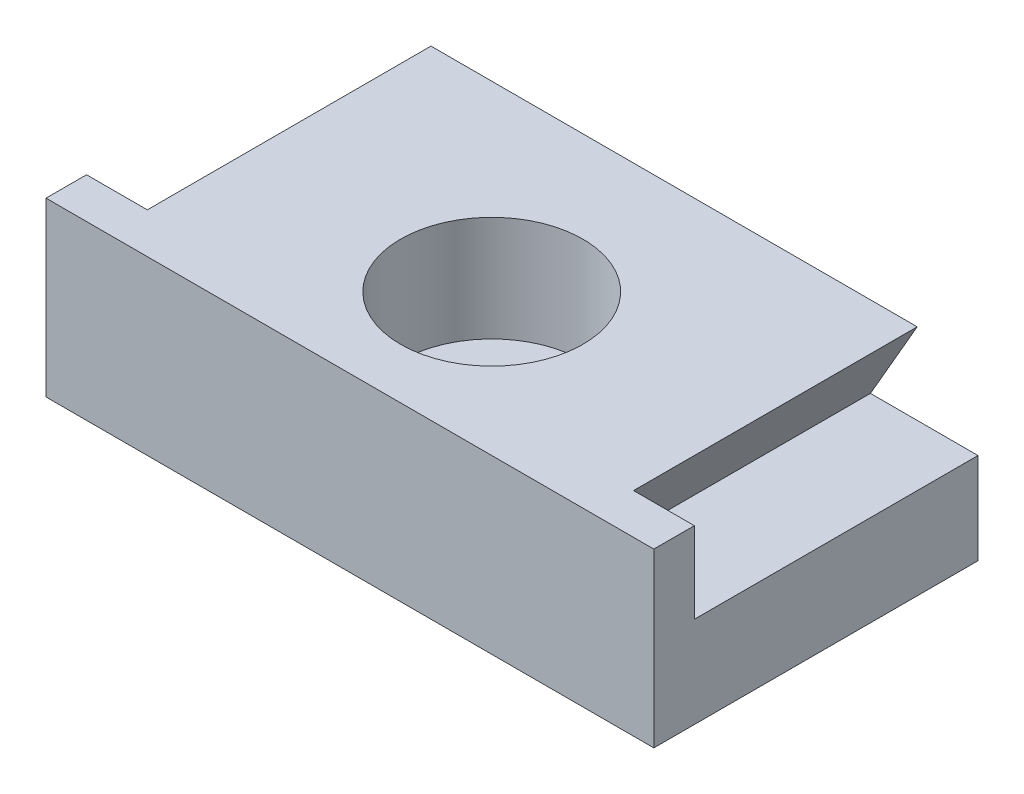
SolidWorks part; units mm, degrees
ref_plane "Front Plane" through (0, 0, 0) normal (0, 0, 1) x (1, 0, 0)
ref_plane "Top Plane" through (0, 0, 0) normal (0, 1, 0) x (1, 0, 0)
ref_plane "Right Plane" through (0, 0, 0) normal (1, 0, 0) x (0, 0, -1)
sketch "Sketch1" plane through (0, 0, 0) normal (0, 1, 0) x (1, 0, 0)
  line L1 (0, 0) -> (30, 0)
  line L2 (0, 0) -> (0, 16)
  line L3 (0, 16) -> (30, 16)
  line L4 (30, 0) -> (30, 16)
  dimension "D1" = 30
  dimension "D2" = 16
extrude "Boss-Extrude1" add sketch "Sketch1" along normal blind 8.5
sketch "Sketch2" plane through (0, 8.5, 0) normal (0, 1, 0) x (1, 0, 0)
  line L0 (0, 0) -> (30, 0) construction
  circle A0 centre (15, 7) radius 4.5
  point P5 (15, 0)
  dimension "D1" = 9
  dimension "D2" = 7
extrude "Cut-Extrude1" cut sketch "Sketch2" against normal blind 5.2
sketch "Sketch3" plane through (0, 3.3, 0) normal (0, 1, 0) x (1, 0, 0)
  circle A0 centre (15, 7) radius 2.65
  circle A1 centre (15, 7) radius 4.5 construction
  circle A2 centre (15, 7) radius 4.5 construction
  dimension "D1" = 5.3
extrude "Cut-Extrude2" cut sketch "Sketch3" against normal through all
sketch "Sketch4" plane through (0, 0, -16) normal (0, 0, -1) x (-1, 0, 0)
  line L0 (-27, 8.5) -> (-24.69, 4.4989)
  line L1 (-30, 8.5) -> (-30, 0) construction
  line L2 (-24.69, 4.4989) -> (-30, 4.4989)
  line L3 (-30, 0) -> (0, 0) construction
  line L4 (-30, 8.5) -> (0, 8.5) construction
  line L5 (-30, 4.4989) -> (-30, 8.5)
  line L6 (-30, 8.5) -> (-27, 8.5)
  line L7 (-15, 8.5) -> (-15, 0) construction
  line L8 (0, 8.5) -> (-3, 8.5)
  line L9 (0, 4.4989) -> (0, 8.5)
  line L10 (-5.31, 4.4989) -> (0, 4.4989)
  line L11 (-3, 8.5) -> (-5.31, 4.4989)
  dimension "D1" = 4.0011
  dimension "D2" = 3
  dimension "D3" = 60
extrude "Cut-Extrude3" cut sketch "Sketch4" against normal blind 14
sketch "Sketch5" plane through (0, 0, -16) normal (0, 0, -1) x (-1, 0, 0)
  line L2 (0, 8.5) -> (0, 0) construction
  line L3 (-15, 8.5) -> (-15, 0) construction
  line L4 (-30, 0) -> (0, 0) construction
  line L5 (-27, 8.5) -> (-3, 8.5) construction
  circle A0 centre (-21.5, 4.25) radius 2.1
  circle A1 centre (-8.5, 4.25) radius 2.1
  point P10 (0, 4.25)
  dimension "D1" = 4.2
  dimension "D2" = 6.5
  dimension "D3" = 4.25
extrude "Cut-Extrude4" cut sketch "Sketch5" against normal blind 7
sketch "Sketch6" plane through (0, 0, 0) normal (0, -1, 0) x (1, 0, 0)
  line L0 (19.8808, -7) -> (10.1192, -7) construction
  circle A0 centre (10.1192, -7) radius 1.1
  circle A1 centre (19.8808, -7) radius 1.1
  circle A2 centre (15, -7) radius 2.65 construction
  circle A3 centre (15, -7) radius 2.65 construction
  point P7 (0, 0)
  point P8 (15, -7)
  dimension "D1" = 2.2
extrude "Cut-Extrude5" cut sketch "Sketch6" against normal blind 2.5
